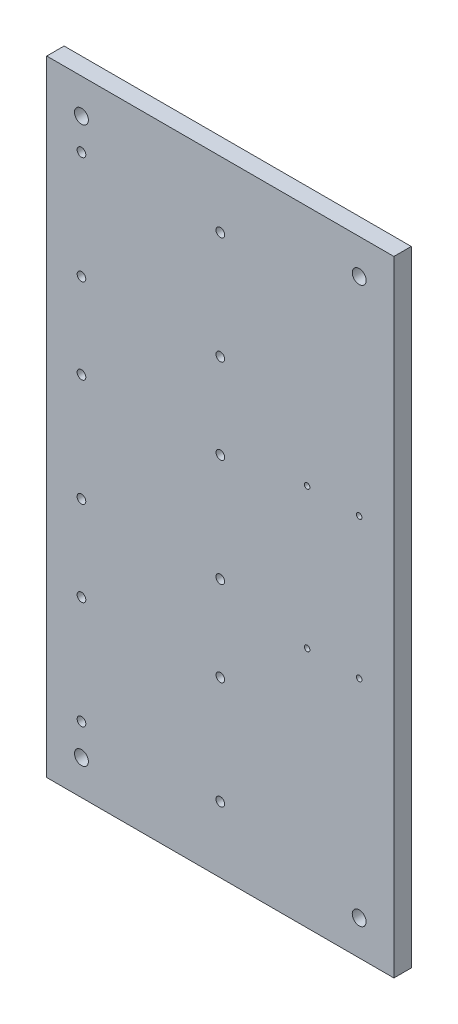
SolidWorks part; units mm, degrees
ref_plane "Plan de face" through (0, 0, 0) normal (0, 0, 1) x (1, 0, 0)
ref_plane "Plan de dessus" through (0, 0, 0) normal (0, 1, 0) x (1, 0, 0)
ref_plane "Plan de droite" through (0, 0, 0) normal (1, 0, 0) x (0, 0, -1)
sketch "Esquisse1" plane through (0, 0, 0) normal (0, 0, 1) x (1, 0, 0)
  line L1 (0, 0) -> (100, 0)
  line L2 (0, 0) -> (0, 180)
  line L3 (0, 180) -> (100, 180)
  line L4 (100, 0) -> (100, 180)
  dimension "D1" = 100
  dimension "D2" = 180
extrude "Boss.-Extru.1" add sketch "Esquisse1" along normal blind 5
sketch "Esquisse2" plane through (0, 0, 5) normal (0, 0, 1) x (1, 0, 0)
  line L0 (0, 90) -> (100, 90) construction
  line L1 (0, 180) -> (0, 0) construction
  line L2 (100, 0) -> (100, 180) construction
  line L3 (10, 105.5) -> (50, 105.5) construction
  line L4 (50, 105.5) -> (50, 90) construction
  line L5 (10, 74.5) -> (50, 74.5) construction
  line L6 (10, 105.5) -> (10, 130) construction
  line L7 (10, 130) -> (50, 130) construction
  line L8 (50, 130) -> (50, 105.5) construction
  line L9 (50, 130) -> (50, 161) construction
  line L10 (50, 161) -> (10, 161) construction
  line L11 (10, 161) -> (10, 130) construction
  line L12 (10, 19) -> (10, 50) construction
  line L13 (50, 19) -> (10, 19) construction
  line L14 (50, 50) -> (50, 19) construction
  line L15 (10, 50) -> (50, 50) construction
  line L16 (75, 110.25) -> (90, 110.25) construction
  line L17 (75, 69.75) -> (90, 69.75) construction
  line L18 (50, 0) -> (50, 5.0098) construction
  line L19 (0, 0) -> (100, 0) construction
  circle A0 centre (10, 105.5) radius 1.25
  circle A1 centre (50, 105.5) radius 1.25
  circle A2 centre (50, 74.5) radius 1.25
  circle A3 centre (10, 74.5) radius 1.25
  circle A4 centre (10, 130) radius 1.25
  circle A5 centre (50, 130) radius 1.25
  circle A6 centre (50, 161) radius 1.25
  circle A7 centre (10, 161) radius 1.25
  circle A8 centre (10, 19) radius 1.25
  circle A9 centre (50, 19) radius 1.25
  circle A10 centre (50, 50) radius 1.25
  circle A11 centre (10, 50) radius 1.25
  circle A12 centre (75, 110.25) radius 0.8
  circle A13 centre (90, 110.25) radius 0.8
  circle A14 centre (90, 69.75) radius 0.8
  circle A15 centre (75, 69.75) radius 0.8
  circle A16 centre (90, 170) radius 2
  circle A17 centre (90, 10) radius 2
  circle A18 centre (10, 170) radius 2
  circle A19 centre (10, 10) radius 2
  dimension "D1" = 31
  dimension "D2" = 40
  dimension "D3" = 2.5
  dimension "D7" = 15
  dimension "D9" = 1.6
  dimension "D11" = 4
  dimension "D4" = 10
  dimension "D5" = 31
  dimension "D6" = 40
  dimension "D8" = 40.5
  dimension "D10" = 10
  dimension "D12" = 80
  dimension "D13" = 40
extrude "Enlèv. mat.-Extru.1" cut sketch "Esquisse2" against normal up to vertex (5 mm away) up to point (100, 180, 0)
